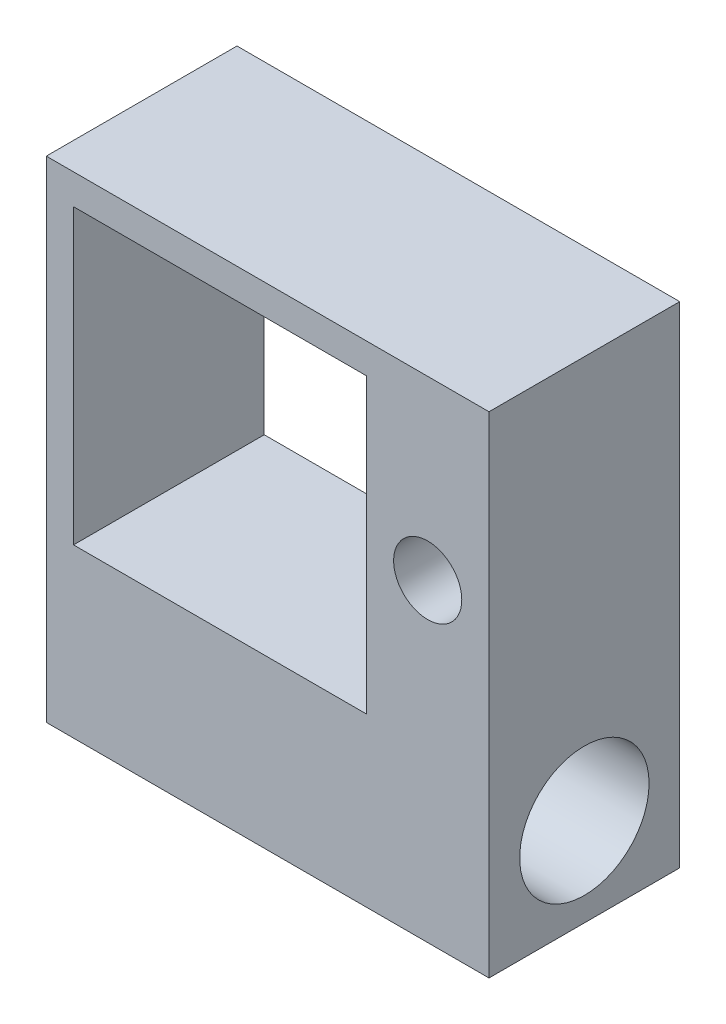
SolidWorks part; units mm, degrees
ref_plane "Front Plane" through (0, 0, 0) normal (0, 0, 1) x (1, 0, 0)
ref_plane "Top Plane" through (0, 0, 0) normal (0, 1, 0) x (1, 0, 0)
ref_plane "Right Plane" through (0, 0, 0) normal (1, 0, 0) x (0, 0, -1)
sketch "Sketch1" plane through (0, 0, 0) normal (0, 0, 1) x (1, 0, 0)
  line L1 (-32.5, -36) -> (32.5, -36)
  line L2 (-32.5, -36) -> (-32.5, 36)
  line L3 (-32.5, 36) -> (32.5, 36)
  line L4 (32.5, -36) -> (32.5, 36)
  line L5 (-32.5, -36) -> (32.5, 36) construction
  line L6 (-32.5, 36) -> (32.5, -36) construction
  line L7 (-28.5, 31.5692) -> (14.5, 31.5692)
  line L8 (-28.5, 31.5692) -> (-28.5, -11.4308)
  line L9 (-28.5, -11.4308) -> (14.5, -11.4308)
  line L10 (14.5, 31.5692) -> (14.5, -11.4308)
  circle A0 centre (23.5, 10.0692) radius 5
  point P0 (0, 0)
  point P12 (14.5, 10.0692)
  point P13 (-7, 10.0692)
  dimension "D3" = 10
  dimension "D7" = 9
  dimension "D1" = 65
  dimension "D2" = 72
  dimension "D4" = 43
  dimension "D5" = 4
  dimension "D6" = 9
  dimension "D8" = 0
  dimension "D9" = 4.4308
  dimension "D10" = 30.5
  dimension "D11" = 43
extrude "Boss-Extrude1" add sketch "Sketch1" along normal blind 28
sketch "Sketch2" plane through (32.5, 0, 0) normal (1, 0, 0) x (0, 0, -1)
  line L0 (-28, -36) -> (0, -36) construction
  circle A0 centre (-14, -23) radius 9.5
  dimension "D1" = 19
  dimension "D2" = 13
extrude "Cut-Extrude1" cut sketch "Sketch2" against normal through all
